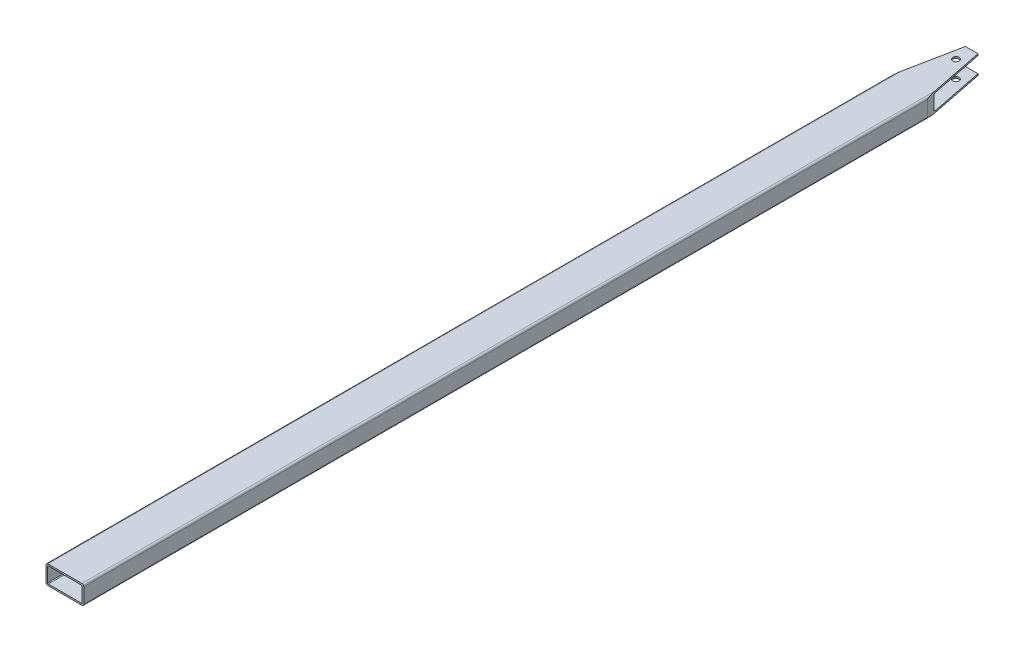
SolidWorks part; units mm, degrees
ref_plane "Front" through (0, 0, 0) normal (0, 0, 1) x (1, 0, 0)
ref_plane "Top" through (0, 0, 0) normal (0, 1, 0) x (1, 0, 0)
ref_plane "Right" through (0, 0, 0) normal (1, 0, 0) x (0, 0, -1)
sketch "Sketch1" plane through (0, 0, 0) normal (0, 0, 1) x (1, 0, 0)
  line L0 (-34.925, 0) -> (-38.1, 0) construction
  line L1 (34.29, -19.05) -> (-34.29, -19.05)
  line L2 (38.1, -15.24) -> (38.1, 15.24)
  line L3 (34.29, 19.05) -> (-34.29, 19.05)
  line L4 (-38.1, -15.24) -> (-38.1, 15.24)
  line L5 (38.1, -19.05) -> (-38.1, 19.05) construction
  line L6 (38.1, 19.05) -> (-38.1, -19.05) construction
  line L7 (33.3375, 15.875) -> (-33.3375, 15.875)
  line L8 (34.925, 14.2875) -> (34.925, -14.2875)
  line L9 (33.3375, -15.875) -> (-33.3375, -15.875)
  line L10 (-34.925, 14.2875) -> (-34.925, -14.2875)
  line L11 (34.925, 15.875) -> (-34.925, -15.875) construction
  line L12 (34.925, -15.875) -> (-34.925, 15.875) construction
  line L13 (0, -15.875) -> (0, -19.05) construction
  line L14 (34.925, -14.2875) -> (34.925, -19.05) construction
  line L16 (34.925, -19.05) -> (38.1, -19.05) construction
  arc A0 (-33.3375, -15.875) -> (-34.925, -14.2875) centre (-33.3375, -14.2875) cw
  arc A1 (34.925, -14.2875) -> (33.3375, -15.875) centre (33.3375, -14.2875) cw
  arc A2 (33.3375, 15.875) -> (34.925, 14.2875) centre (33.3375, 14.2875) cw
  arc A3 (-33.3375, 15.875) -> (-34.925, 14.2875) centre (-33.3375, 14.2875) ccw
  arc A4 (34.29, -19.05) -> (38.1, -15.24) centre (34.29, -15.24) ccw
  arc A5 (38.1, 15.24) -> (34.29, 19.05) centre (34.29, 15.24) ccw
  arc A6 (-34.29, 19.05) -> (-38.1, 15.24) centre (-34.29, 15.24) ccw
  arc A7 (-34.29, -19.05) -> (-38.1, -15.24) centre (-34.29, -15.24) cw
  point P0 (0, 0)
  point P6 (0, 0)
  dimension "D2" = 1.5875
  dimension "D3" = 3.81
sketch "Sketch2" plane through (0, 0, 0) normal (1, 0, 0) x (0, 0, -1)
  line L0 (-914.4, 0) -> (914.4, 0) construction
  dimension "Length" = 1828.8
ref_plane "Plane1" through (38.1, 0, 0) normal (1, 0, 0) x (0, 0, -1)
sketch "Sketch5" plane through (38.1, 0, 0) normal (1, 0, 0) x (0, 0, -1)
  line L0 (-914.4, 19.05) -> (-914.4, -19.05) construction
  line L1 (914.4, 19.05) -> (914.4, -19.05) construction
sketch "Sketch4" plane through (0, 0, 0) normal (0, 0, 1) x (1, 0, 0)
  line L0 (38.1, -15.24) -> (38.1, 15.24) construction
  line L1 (34.29, 19.05) -> (-34.29, 19.05) construction
  line L2 (-38.1, -15.24) -> (-38.1, 15.24) construction
  line L3 (34.29, -19.05) -> (-34.29, -19.05) construction
  line L4 (34.925, 14.2875) -> (34.925, -14.2875) construction
  line L5 (33.3375, -15.875) -> (-33.3375, -15.875) construction
  line L6 (-34.925, 14.2875) -> (-34.925, -14.2875) construction
  line L7 (33.3375, 15.875) -> (-33.3375, 15.875) construction
  line L8 (38.1, -15.24) -> (38.1, 15.24)
  line L9 (34.29, 19.05) -> (-34.29, 19.05)
  line L10 (-38.1, -15.24) -> (-38.1, 15.24)
  line L11 (34.29, -19.05) -> (-34.29, -19.05)
  line L12 (34.925, 14.2875) -> (34.925, -14.2875)
  line L13 (33.3375, -15.875) -> (-33.3375, -15.875)
  line L14 (-34.925, 14.2875) -> (-34.925, -14.2875)
  line L15 (33.3375, 15.875) -> (-33.3375, 15.875)
  arc A0 (38.1, 15.24) -> (34.29, 19.05) centre (34.29, 15.24) ccw construction
  arc A1 (-34.29, 19.05) -> (-38.1, 15.24) centre (-34.29, 15.24) ccw construction
  arc A2 (-38.1, -15.24) -> (-34.29, -19.05) centre (-34.29, -15.24) ccw construction
  arc A3 (34.29, -19.05) -> (38.1, -15.24) centre (34.29, -15.24) ccw construction
  arc A4 (33.3375, -15.875) -> (34.925, -14.2875) centre (33.3375, -14.2875) ccw construction
  arc A5 (-34.925, -14.2875) -> (-33.3375, -15.875) centre (-33.3375, -14.2875) ccw construction
  arc A6 (-33.3375, 15.875) -> (-34.925, 14.2875) centre (-33.3375, 14.2875) ccw construction
  arc A7 (34.925, 14.2875) -> (33.3375, 15.875) centre (33.3375, 14.2875) ccw construction
  arc A8 (38.1, 15.24) -> (34.29, 19.05) centre (34.29, 15.24) ccw
  arc A9 (-34.29, 19.05) -> (-38.1, 15.24) centre (-34.29, 15.24) ccw
  arc A10 (-38.1, -15.24) -> (-34.29, -19.05) centre (-34.29, -15.24) ccw
  arc A11 (34.29, -19.05) -> (38.1, -15.24) centre (34.29, -15.24) ccw
  arc A12 (33.3375, -15.875) -> (34.925, -14.2875) centre (33.3375, -14.2875) ccw
  arc A13 (-34.925, -14.2875) -> (-33.3375, -15.875) centre (-33.3375, -14.2875) ccw
  arc A14 (-33.3375, 15.875) -> (-34.925, 14.2875) centre (-33.3375, 14.2875) ccw
  arc A15 (34.925, 14.2875) -> (33.3375, 15.875) centre (33.3375, 14.2875) ccw
extrude "Boss-Extrude1" add sketch "Sketch4" along normal up to vertex (914.4 mm away) and the other way up to vertex (914.4 mm away) up to point (0, 0, 914.4) other way up to point (0, 0, -914.4)
sketch "Sketch7" plane through (0, 19.05, 0) normal (0, 1, 0) x (1, 0, 0)
  line L0 (-38.1, 914.4) -> (38.1, 914.4) construction
  line L1 (-12.7, 914.4) -> (12.7, 914.4) construction
  line L2 (12.7, 914.4) -> (38.1, 787.4)
  line L3 (38.1, -914.4) -> (38.1, 914.4) construction
  line L4 (38.1, 787.4) -> (38.1, 914.4)
  line L5 (38.1, 914.4) -> (12.7, 914.4)
  line L6 (-12.7, 914.4) -> (-38.1, 914.4)
  line L7 (-38.1, 914.4) -> (-38.1, 787.4)
  line L8 (-38.1, -914.4) -> (-38.1, 914.4) construction
  line L9 (-38.1, 787.4) -> (-12.7, 914.4)
  line L10 (0, 914.4) -> (0, 882.65) construction
  circle A0 centre (0, 882.65) radius 6.35
  point P7 (0, 914.4)
  dimension "D4" = 12.7
  dimension "D1" = 127
  dimension "D2" = 25.4
  dimension "D3" = 31.75
extrude "Cut-Extrude1" cut sketch "Sketch7" against normal through all
equation "\"D3@Sketch1\"=\"Outside Width@Sketch1\"*.05"
equation "\"D2@Sketch1\"=\"D1@Sketch1\"*.05"
